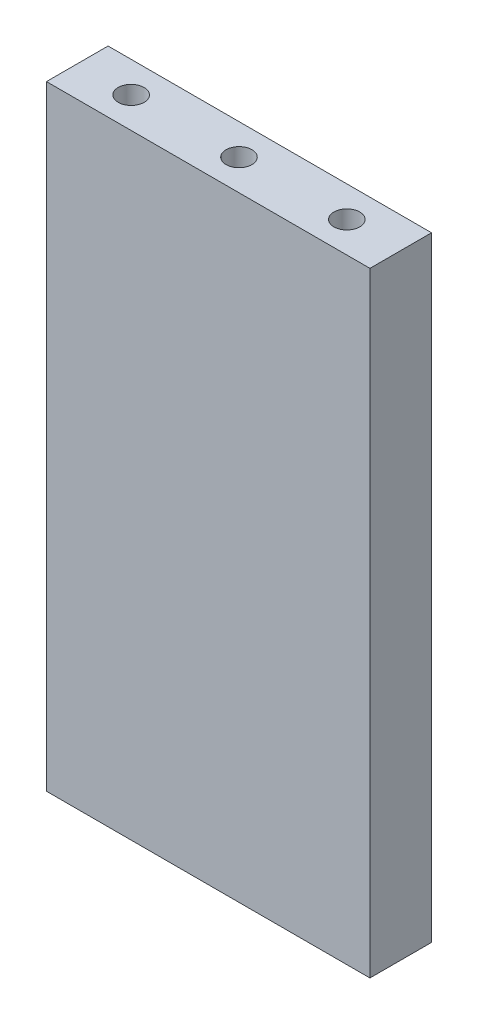
SolidWorks part; units mm, degrees
ref_plane "Front Plane" through (0, 0, 0) normal (0, 0, 1) x (1, 0, 0)
ref_plane "Top Plane" through (0, 0, 0) normal (0, 1, 0) x (1, 0, 0)
ref_plane "Right Plane" through (0, 0, 0) normal (1, 0, 0) x (0, 0, -1)
sketch "Sketch1" plane through (0, 0, 0) normal (0, 0, 1) x (1, 0, 0)
  line L1 (-25, -47.5) -> (25, -47.5)
  line L2 (-25, -47.5) -> (-25, 47.5)
  line L3 (-25, 47.5) -> (25, 47.5)
  line L4 (25, -47.5) -> (25, 47.5)
  line L5 (-25, -47.5) -> (25, 47.5) construction
  line L6 (-25, 47.5) -> (25, -47.5) construction
  point P0 (0, 0)
  dimension "D1" = 95
  dimension "D2" = 50
extrude "Boss-Extrude1" add sketch "Sketch1" against normal blind 9.525
sketch "Sketch2" plane through (0, 47.5, 0) normal (0, 1, 0) x (1, 0, 0)
  point P0 (0, 4.7625)
  point P1 (16.67, 4.7625)
  point P2 (-16.67, 4.7625)
  dimension "D1" = 4.7625
  dimension "D2" = 16.67
  dimension "D3" = 16.67
sketch "Sketch3" plane through (0, -47.5, 0) normal (0, -1, 0) x (1, 0, 0)
  point P0 (16.67, -4.7625)
  point P2 (0, -4.7625)
  point P4 (-16.67, -4.7625)
hole_wizard "Ø4.0mm Dowel Hole1" positions "Sketch2" profile "Sketch5" hole size "Ø4.0" standard "ANSI Metric"
sketch "Sketch5" plane through (0, 47.5, -4.7625) normal (1, 0, 0) x (0, 0, 1)
  line L0 (0, 0) -> (0, 4.4017)
  line L1 (0, 4.4017) -> (2, 3.2)
  line L2 (2, 3.2) -> (2, 0)
  line L5 (2, 0) -> (0, 0)
  line L10 (0, 4.4017) -> (-2, 3.2) construction
  line L11 (0, -6.35) -> (0, 107.95) construction
  dimension "Hole Dia." = 4
  dimension "Hole Depth" = 3.2
  dimension "Drill Angle" = 118
hole_wizard "Ø4.0mm Dowel Hole2" positions "Sketch3" profile "Sketch6" hole size "Ø4.0" standard "ANSI Metric"
sketch "Sketch6" plane through (16.67, -47.5, -4.7625) normal (1, 0, 0) x (0, 0, -1)
  line L0 (0, 0) -> (0, 4.4017)
  line L1 (0, 4.4017) -> (2, 3.2)
  line L2 (2, 3.2) -> (2, 0)
  line L5 (2, 0) -> (0, 0)
  line L10 (0, 4.4017) -> (-2, 3.2) construction
  line L11 (0, -6.35) -> (0, 107.95) construction
  dimension "Hole Dia." = 4
  dimension "Hole Depth" = 3.2
  dimension "Drill Angle" = 118
